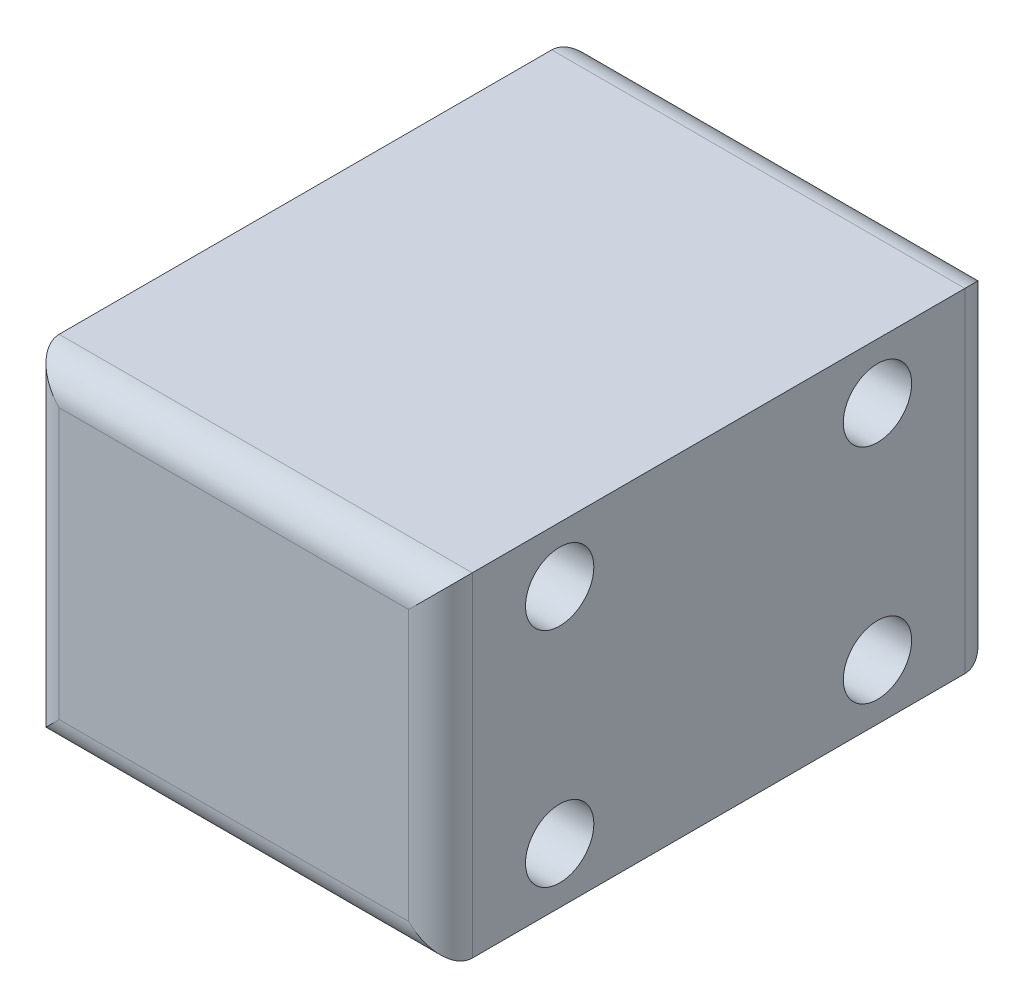
SolidWorks part; units mm, degrees
ref_plane "前视基准面" through (0, 0, 0) normal (0, 0, 1) x (1, 0, 0)
ref_plane "上视基准面" through (0, 0, 0) normal (0, 1, 0) x (1, 0, 0)
ref_plane "右视基准面" through (0, 0, 0) normal (1, 0, 0) x (0, 0, -1)
other "Configuration Table"
sketch "草图1" plane through (0, 0, 0) normal (0, 0, 1) x (1, 0, 0)
  line L1 (0, 0) -> (-26, 0)
  line L2 (0, 0) -> (0, 21)
  line L3 (0, 21) -> (-26, 21)
  line L4 (-26, 0) -> (-26, 21)
  dimension "D1" = 21
  dimension "D2" = 26
extrude "凸台-拉伸1" add sketch "草图1" along normal blind 35
sketch "草图2" plane through (0, 0, 0) normal (1, 0, 0) x (0, 0, -1)
  line L0 (-17.5, 0) -> (-17.5, 23.6601) construction
  line L1 (-35, 0) -> (0, 0) construction
  line L2 (0, 10.5) -> (-35, 10.5) construction
  line L3 (0, 0) -> (0, 21) construction
  line L4 (-35, 0) -> (-35, 21) construction
  circle A0 centre (-27.5, 17.5) radius 2.15
  circle A1 centre (-27.5, 3.5) radius 2.15
  circle A2 centre (-7.5, 17.5) radius 2.15
  circle A3 centre (-7.5, 3.5) radius 2.15
  dimension "D1" = 4.3
  dimension "D2" = 20
  dimension "D3" = 14
extrude "切除-拉伸1" cut sketch "草图2" against normal up to next
fillet "圆角1" radius 2 8 edges at (-13, 21, 0) (-26, 10.5, 0) (-13, 0, 0) (0, 10.5, 0) (-13, 0, 35) (-26, 10.5, 35) (-13, 21, 35) (0, 10.5, 35)
